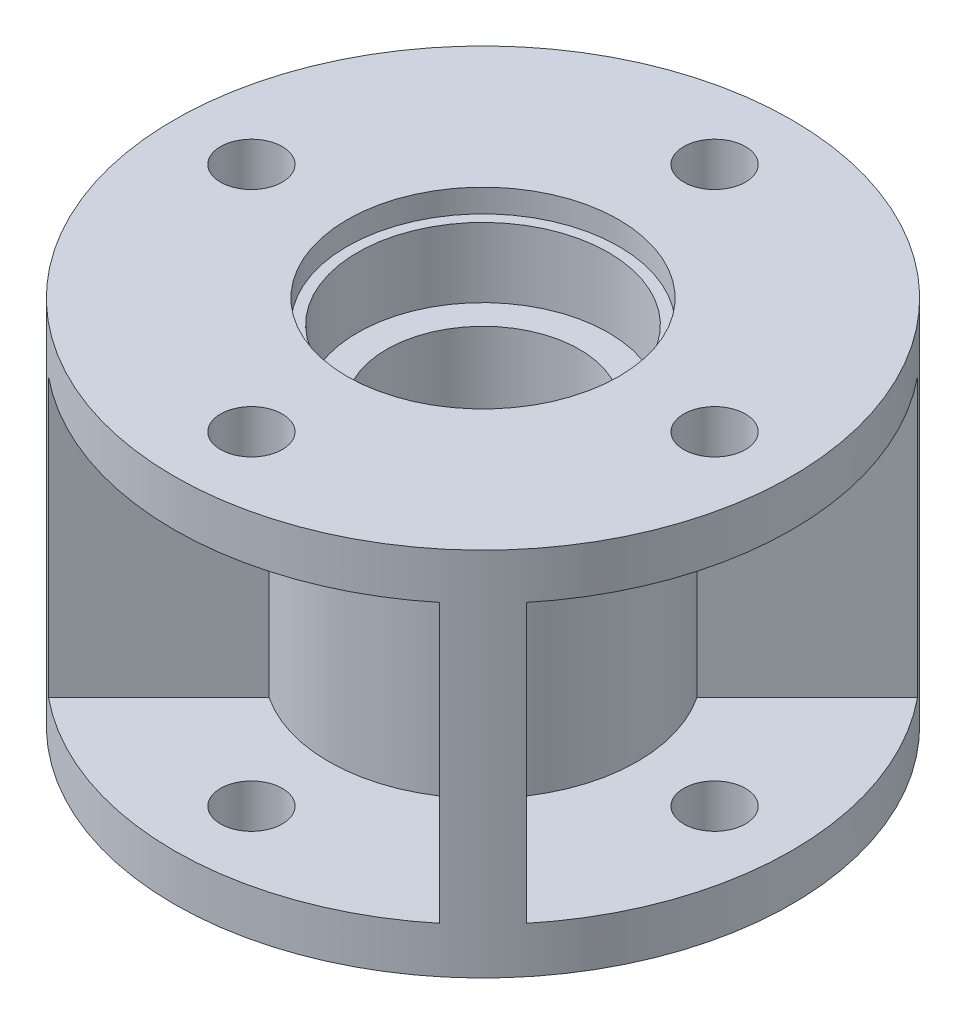
SolidWorks part; units mm, degrees
ref_plane "Front Plane" through (0, 0, 0) normal (0, 0, 1) x (1, 0, 0)
ref_plane "Top Plane" through (0, 0, 0) normal (0, 1, 0) x (1, 0, 0)
ref_plane "Right Plane" through (0, 0, 0) normal (1, 0, 0) x (0, 0, -1)
sketch "Sketch1" plane through (0, 0, 0) normal (0, 1, 0) x (1, 0, 0)
  circle A0 centre (0, 0) radius 12.5
  circle A1 centre (0, 0) radius 40
  dimension "D1" = 25
  dimension "D2" = 80
extrude "Boss-Extrude1" add sketch "Sketch1" along normal blind 6
sketch "Sketch3" plane through (0, 6, 0) normal (0, 1, 0) x (1, 0, 0)
  circle A0 centre (0, 0) radius 12.5
  circle A1 centre (0, 0) radius 20
  circle A2 centre (0, 0) radius 12.5 construction
  dimension "D1" = 40
extrude "Boss-Extrude2" add sketch "Sketch3" along normal blind 30
sketch "Sketch4" plane through (0, 36, 0) normal (0, 1, 0) x (1, 0, 0)
  circle A0 centre (0, 0) radius 16.25
  circle A1 centre (0, 0) radius 20
  circle A2 centre (0, 0) radius 20 construction
  dimension "D1" = 32.5
extrude "Boss-Extrude3" add sketch "Sketch4" along normal blind 12
sketch "Sketch5" plane through (0, 6, 0) normal (0, 1, 0) x (1, 0, 0)
  line L0 (0, 0) -> (-28.2843, -28.2843) construction
  line L1 (0, 0) -> (-24.4998, 0) construction
  line L2 (-16.6848, -11.028) -> (-30.9709, -25.3141)
  line L3 (-11.028, -16.6848) -> (-25.3141, -30.9709)
  line L4 (-16.6848, 11.028) -> (-30.9709, 25.3141)
  line L5 (-11.028, 16.6848) -> (-25.3141, 30.9709)
  line L6 (11.028, 16.6848) -> (25.3141, 30.9709)
  line L7 (16.6848, 11.028) -> (30.9709, 25.3141)
  line L8 (16.6848, -11.028) -> (30.9709, -25.3141)
  line L9 (11.028, -16.6848) -> (25.3141, -30.9709)
  arc A0 (-16.6848, -11.028) -> (-11.028, -16.6848) centre (0, 0) ccw
  circle A1 centre (0, 0) radius 20 construction
  arc A2 (-30.9709, -25.3141) -> (-25.3141, -30.9709) centre (0, 0) ccw
  circle A3 centre (0, 0) radius 40 construction
  arc A4 (-25.3141, 30.9709) -> (-30.9709, 25.3141) centre (0, 0) ccw
  arc A5 (-11.028, 16.6848) -> (-16.6848, 11.028) centre (0, 0) ccw
  arc A6 (30.9709, 25.3141) -> (25.3141, 30.9709) centre (0, 0) ccw
  arc A7 (16.6848, 11.028) -> (11.028, 16.6848) centre (0, 0) ccw
  arc A8 (25.3141, -30.9709) -> (30.9709, -25.3141) centre (0, 0) ccw
  arc A9 (11.028, -16.6848) -> (16.6848, -11.028) centre (0, 0) ccw
  point P10 (-14.1421, -14.1421)
  point P28 (0, 0)
  dimension "D1" = 45
  dimension "D2" = 8
  dimension "D3" = 4
extrude "Boss-Extrude4" add sketch "Sketch5" along normal up to surface (42 mm away) up to face at (0, 48, 20)
sketch "Sketch6" plane through (0, 48, 0) normal (0, 1, 0) x (1, 0, 0)
  circle A0 centre (0, 0) radius 17.6
  dimension "D1" = 35.2
extrude "Cut-Extrude2" cut sketch "Sketch6" against normal blind 3
sketch "Sketch7" plane through (0, 48, 0) normal (0, 1, 0) x (1, 0, 0)
  circle A0 centre (0, 0) radius 40
  circle A1 centre (0, 0) radius 20
  arc A2 (-25.3141, 30.9709) -> (-30.9709, 25.3141) centre (0, 0) ccw construction
  arc A3 (-16.6848, 11.028) -> (-16.6848, -11.028) centre (0, 0) ccw construction
extrude "Boss-Extrude5" add sketch "Sketch7" against normal blind 6
sketch "Sketch2" plane through (0, 0, 0) normal (0, 1, 0) x (1, 0, 0)
  circle A0 centre (0, 30) radius 4
  circle A1 centre (30, 0) radius 4
  circle A2 centre (0, -30) radius 4
  circle A3 centre (-30, 0) radius 4
  point P12 (0, 0)
  dimension "D1" = 8
  dimension "D2" = 30
  dimension "D3" = 4
extrude "Cut-Extrude1" cut sketch "Sketch2" along normal up to surface (48 mm away) up to face at (0, 48, 40)
